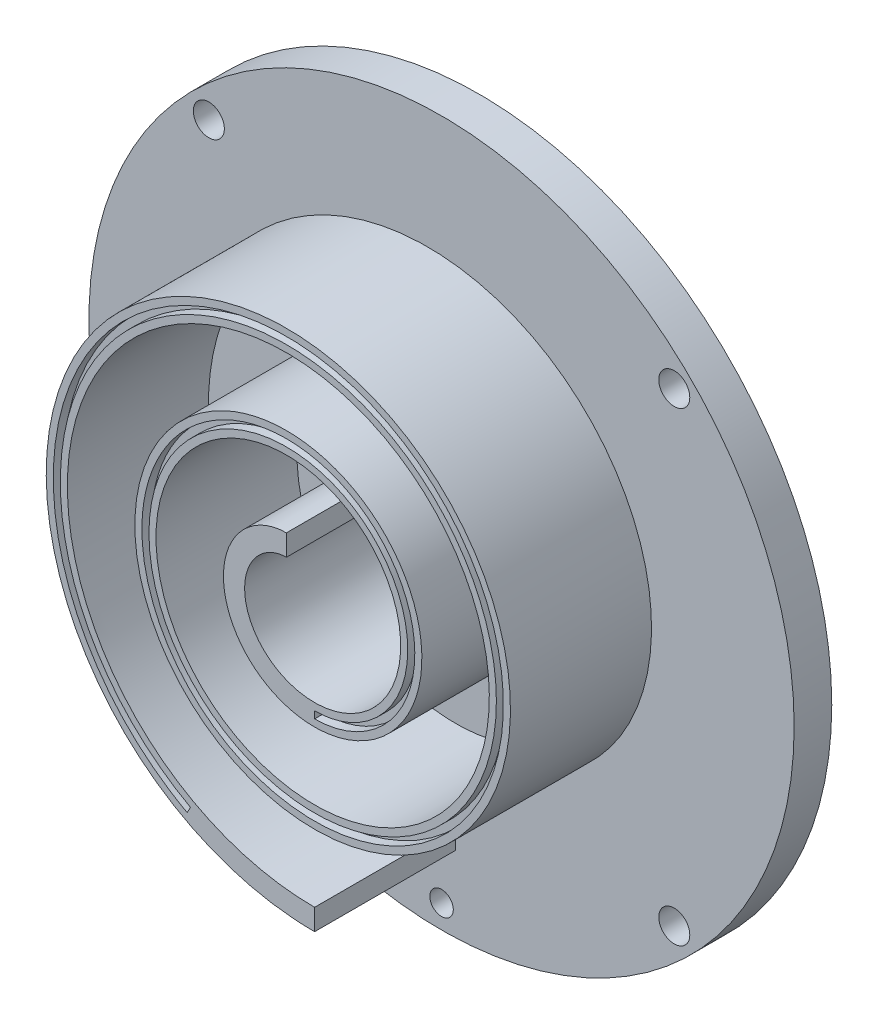
SolidWorks part; units mm, degrees
ref_plane "前视基准面" through (0, 0, 0) normal (0, 0, 1) x (1, 0, 0)
ref_plane "上视基准面" through (0, 0, 0) normal (0, 1, 0) x (1, 0, 0)
ref_plane "右视基准面" through (0, 0, 0) normal (1, 0, 0) x (0, 0, -1)
sketch "草图1" plane through (0, 0, 0) normal (0, 0, 1) x (1, 0, 0)
  circle A0 centre (0, 0) radius 75
extrude "凸台-拉伸1" add sketch "草图1" along normal blind 8
ref_plane "基准面1" through (0, 0, 8) normal (0, 0, 1) x (1, 0, 0)
sketch "草图2" plane through (0, 0, 8) normal (0, 0, 1) x (1, 0, 0)
  line L0 (3, -54.2987) -> (3, -58.7973)
  line L1 (3, -58.7973) -> (3, -58.7987)
  line L2 (-3, 11.6748) -> (-3, 7.1747)
  spline S0 degree 3 poles (-3, 7.1747) (-3.301, 7.1637) (-3.9181, 7.1413) (-4.8518, 6.9591) (-5.8002, 6.6592) (-6.7457, 6.224) (-7.6694, 5.6534) (-8.5516, 4.9455) (-9.3721, 4.1026) (-9.9821, 3.299) (-10.4206, 2.5966) (-10.7247, 2.0355) (-10.9986, 1.4466) (-11.2401, 0.8315) (-11.4468, 0.192) (-11.6168, -0.4699) (-11.7479, -1.1521) (-11.8385, -1.8523) (-11.8867, -2.568) (-11.891, -3.2966) (-11.85, -4.0353) (-11.7624, -4.7814) (-11.6273, -5.5319) (-11.4437, -6.2836) (-11.211, -7.0334) (-10.9288, -7.7781) (-10.5968, -8.5144) (-10.215, -9.239) (-9.7837, -9.9485) (-9.3031, -10.6394) (-8.7742, -11.3084) (-8.1976, -11.9522) (-7.5746, -12.5673) (-6.9066, -13.1506) (-6.1951, -13.6986) (-5.442, -14.2083) (-4.6493, -14.6767) (-3.8193, -15.1007) (-2.9545, -15.4775) (-2.0576, -15.8044) (-1.1316, -16.0789) (-0.1794, -16.2987) (0.7956, -16.4616) (1.79, -16.5655) (2.8002, -16.6087) (3.8224, -16.5898) (4.8528, -16.5072) (5.8874, -16.3601) (6.9221, -16.1475) (7.9527, -15.8689) (8.975, -15.524) (9.9847, -15.1128) (10.9775, -14.6356) (11.949, -14.0929) (12.8949, -13.4855) (13.8109, -12.8146) (14.6927, -12.0816) (15.5361, -11.2882) (16.3371, -10.4363) (17.0915, -9.5281) (17.7955, -8.5663) (18.4453, -7.5537) (19.0373, -6.4932) (19.568, -5.3883) (20.0342, -4.2424) (20.433, -3.0593) (20.7613, -1.8432) (21.0167, -0.5981) (21.1969, 0.6715) (21.2998, 1.961) (21.3237, 3.2657) (21.267, 4.5807) (21.1286, 5.901) (20.9076, 7.2214) (20.6036, 8.5368) (20.2162, 9.842) (19.7457, 11.1315) (19.1924, 12.4001) (18.5573, 13.6425) (17.8414, 14.8533) (17.0463, 16.0273) (16.1738, 17.1593) (15.2261, 18.2442) (14.2057, 19.2769) (13.1155, 20.2527) (11.9586, 21.1668) (10.7386, 22.0146) (9.4592, 22.792) (8.1246, 23.4947) (6.7391, 24.1188) (5.3073, 24.6609) (3.8343, 25.1174) (2.325, 25.4855) (0.7848, 25.7623) (-0.7806, 25.9454) (-2.3656, 26.0329) (-3.9643, 26.0229) (-5.5706, 25.9141) (-7.1785, 25.7056) (-8.7816, 25.3968) (-10.3737, 24.9874) (-11.9485, 24.4777) (-13.4996, 23.8682) (-15.0206, 23.16) (-16.5053, 22.3545) (-17.9474, 21.4535) (-19.3407, 20.4591) (-20.6791, 19.3741) (-21.9569, 18.2014) (-23.1682, 16.9445) (-24.3074, 15.607) (-25.3693, 14.1931) (-26.3487, 12.7074) (-27.2408, 11.1546) (-28.041, 9.5399) (-28.7451, 7.8687) (-29.3491, 6.1469) (-29.8495, 4.3803) (-30.243, 2.5754) (-30.5268, 0.7386) (-30.6985, -1.1234) (-30.756, -3.0038) (-30.6978, -4.8954) (-30.5226, -6.7911) (-30.2298, -8.6837) (-29.8191, -10.5659) (-29.2907, -12.4301) (-28.6452, -14.2692) (-27.8838, -16.0756) (-27.008, -17.842) (-26.0199, -19.5612) (-24.922, -21.226) (-23.7173, -22.8294) (-22.4092, -24.3645) (-21.0017, -25.8246) (-19.4989, -27.2033) (-17.9056, -28.4944) (-16.2269, -29.6919) (-14.4684, -30.7902) (-12.6359, -31.784) (-10.7357, -32.6683) (-8.7743, -33.4386) (-6.7586, -34.0906) (-4.6958, -34.6206) (-2.5932, -35.0253) (-0.4586, -35.3017) (1.7002, -35.4474) (3.8752, -35.4606) (6.0582, -35.3398) (8.2408, -35.084) (10.4149, -34.6928) (12.5718, -34.1664) (14.7032, -33.5054) (16.8005, -32.7109) (18.8556, -31.7846) (20.8599, -30.7288) (22.8054, -29.5463) (24.684, -28.2402) (26.4879, -26.8143) (28.2093, -25.273) (29.8409, -23.621) (31.3756, -21.8635) (32.8065, -20.0063) (34.1272, -18.0555) (35.3315, -16.0176) (36.4138, -13.8996) (37.3686, -11.709) (38.1912, -9.4532) (38.8771, -7.1405) (39.4224, -4.779) (39.8238, -2.3774) (40.0784, 0.0556) (40.1837, 2.5108) (40.1381, 4.9792) (39.9403, 7.4515) (39.5897, 9.9181) (39.0862, 12.3697) (38.4304, 14.7967) (37.6234, 17.1896) (36.6669, 19.539) (35.5632, 21.8355) (34.3153, 24.0698) (32.9267, 26.233) (31.4013, 28.316) (30.0215, 29.9762) (28.8545, 31.2558) (27.9473, 32.1913) (27.0097, 33.1004) (26.0427, 33.9823) (25.0468, 34.836) (24.0231, 35.6605) (22.9723, 36.4549) (21.8953, 37.2183) (20.7931, 37.9499) (19.6665, 38.6488) (18.5166, 39.3143) (17.3443, 39.9455) (16.1507, 40.5417) (14.9368, 41.1022) (13.7037, 41.6263) (12.4524, 42.1133) (11.1841, 42.5627) (9.9, 42.9738) (8.6011, 43.3462) (7.2887, 43.6792) (5.964, 43.9724) (4.628, 44.2253) (3.2822, 44.4376) (1.9277, 44.6089) (0.5658, 44.7388) (-0.8024, 44.827) (-2.1753, 44.8733) (-3.5519, 44.8775) (-4.9308, 44.8394) (-6.3107, 44.7589) (-7.6903, 44.6358) (-9.0683, 44.4701) (-10.4433, 44.2618) (-11.814, 44.0109) (-13.1792, 43.7175) (-14.5375, 43.3817) (-15.8876, 43.0036) (-17.2281, 42.5834) (-18.5578, 42.1214) (-19.8753, 41.6178) (-21.1793, 41.0729) (-22.4686, 40.4871) (-23.7419, 39.8608) (-24.9978, 39.1944) (-26.2352, 38.4884) (-27.4527, 37.7433) (-28.6492, 36.9597) (-29.8233, 36.1381) (-30.974, 35.2792) (-32.1, 34.3836) (-33.2002, 33.4521) (-34.2734, 32.4854) (-35.3184, 31.4842) (-36.3342, 30.4495) (-37.3197, 29.382) (-38.2739, 28.2827) (-39.1957, 27.1524) (-40.0841, 25.9922) (-40.9381, 24.8029) (-41.7568, 23.5857) (-42.5393, 22.3415) (-43.2847, 21.0715) (-43.9922, 19.7767) (-44.6608, 18.4583) (-45.2899, 17.1175) (-45.8788, 15.7554) (-46.4265, 14.3733) (-46.9326, 12.9723) (-47.3964, 11.5538) (-47.8172, 10.1191) (-48.1946, 8.6693) (-48.5279, 7.206) (-48.8167, 5.7303) (-49.0605, 4.2437) (-49.259, 2.7475) (-49.4119, 1.243) (-49.5187, -0.2682) (-49.5791, -1.7847) (-49.5931, -3.3053) (-49.5604, -4.8284) (-49.4808, -6.3526) (-49.3543, -7.8764) (-49.1807, -9.3985) (-48.9602, -10.9173) (-48.6926, -12.4314) (-48.3782, -13.9394) (-48.017, -15.4397) (-47.6092, -16.931) (-47.155, -18.4118) (-46.6547, -19.8806) (-46.1086, -21.336) (-45.5171, -22.7766) (-44.8804, -24.201) (-44.1992, -25.6077) (-43.4738, -26.9953) (-42.7048, -28.3625) (-41.8927, -29.7079) (-41.0383, -31.0301) (-40.1421, -32.3278) (-39.2048, -33.5997) (-38.2272, -34.8444) (-37.21, -36.0608) (-36.1542, -37.2474) (-35.0605, -38.4032) (-33.9299, -39.5269) (-32.7633, -40.6173) (-31.5616, -41.6733) (-30.326, -42.6937) (-29.0574, -43.6774) (-27.7569, -44.6235) (-26.4257, -45.5308) (-25.0649, -46.3983) (-23.6757, -47.2251) (-22.2593, -48.0104) (-20.817, -48.753) (-19.3501, -49.4523) (-17.8598, -50.1075) (-16.3475, -50.7176) (-14.8145, -51.2821) (-13.2623, -51.8001) (-11.6922, -52.2711) (-10.1056, -52.6945) (-8.5041, -53.0696) (-6.889, -53.396) (-5.262, -53.6732) (-3.6243, -53.9006) (-1.9777, -54.0783) (-0.3236, -54.2046) (1.3365, -54.2839) (2.4452, -54.2938) (3, -54.2987) knots 0 0 0 0 0.001869 0.003832 0.005889 0.008039 0.010283 0.01262 0.01505 0.017575 0.018872 0.020194 0.021538 0.022906 0.024297 0.025712 0.02715 0.028612 0.030097 0.031605 0.033137 0.034692 0.03627 0.037872 0.039498 0.041146 0.042818 0.044514 0.046233 0.047975 0.04974 0.051529 0.053342 0.055178 0.057037 0.05892 0.060825 0.062755 0.064708 0.066684 0.068683 0.070706 0.072753 0.074822 0.076916 0.079032 0.081172 0.083335 0.085522 0.087732 0.089966 0.092223 0.094503 0.096807 0.099134 0.101484 0.103858 0.106255 0.108676 0.11112 0.113587 0.116078 0.118592 0.12113 0.123691 0.126275 0.128883 0.131514 0.134169 0.136847 0.139548 0.142273 0.145021 0.147793 0.150587 0.153406 0.156248 0.159113 0.162001 0.164913 0.167848 0.170807 0.173789 0.176795 0.179823 0.182876 0.185951 0.18905 0.192173 0.195319 0.198488 0.20168 0.204896 0.208136 0.211399 0.214685 0.217994 0.221327 0.224684 0.228063 0.231467 0.234893 0.238343 0.241816 0.245313 0.248833 0.252377 0.255944 0.259534 0.263148 0.266785 0.270445 0.274129 0.277836 0.281567 0.285321 0.289098 0.292899 0.296723 0.300571 0.304442 0.308337 0.312254 0.316195 0.32016 0.324148 0.328159 0.332194 0.336252 0.340334 0.344439 0.348567 0.352719 0.356894 0.361093 0.365314 0.36956 0.373828 0.37812 0.382436 0.386775 0.391137 0.395523 0.399932 0.404364 0.40882 0.413299 0.417802 0.422328 0.426877 0.43145 0.436046 0.440666 0.445309 0.449975 0.454665 0.459378 0.464115 0.468875 0.473658 0.478465 0.483295 0.488148 0.493025 0.497926 0.502849 0.507796 0.512767 0.517761 0.522778 0.527819 0.532883 0.53797 0.543081 0.548215 0.553373 0.558554 0.563758 0.568986 0.574237 0.579512 0.58481 0.590131 0.595476 0.600844 0.603537 0.606236 0.608941 0.611652 0.614369 0.617091 0.619819 0.622553 0.625293 0.628039 0.630791 0.633548 0.636312 0.639081 0.641856 0.644637 0.647424 0.650216 0.653015 0.655819 0.658629 0.661445 0.664267 0.667095 0.669928 0.672768 0.675613 0.678464 0.681321 0.684184 0.687052 0.689927 0.692807 0.695693 0.698585 0.701483 0.704387 0.707297 0.710212 0.713133 0.71606 0.718993 0.721932 0.724877 0.727827 0.730784 0.733746 0.736714 0.739688 0.742668 0.745653 0.748645 0.751642 0.754645 0.757654 0.760669 0.76369 0.766717 0.769749 0.772787 0.775831 0.778881 0.781937 0.784999 0.788066 0.79114 0.794219 0.797304 0.800395 0.803491 0.806594 0.809703 0.812817 0.815937 0.819063 0.822195 0.825332 0.828476 0.831625 0.834781 0.837942 0.841109 0.844281 0.84746 0.850645 0.853835 0.857031 0.860233 0.863441 0.866655 0.869874 0.8731 0.876331 0.879568 0.882811 0.88606 0.889315 0.892575 0.895841 0.899114 0.902392 0.905676 0.908965 0.912261 0.915563 0.91887 0.922183 0.925502 0.928827 0.932158 0.935494 0.938837 0.942185 0.945539 0.948899 0.952265 0.955636 0.959014 0.962397 0.965786 0.969181 0.972582 0.975989 0.979402 0.98282 0.986244 0.989674 0.99311 0.996552 1 1 1 1
  spline S1 degree 3 poles (3, -58.7987) (2.3992, -58.7934) (1.1984, -58.7827) (-0.5996, -58.6968) (-2.3914, -58.56) (-4.1753, -58.3675) (-5.9497, -58.121) (-7.7129, -57.8207) (-9.4632, -57.4669) (-11.1992, -57.0603) (-12.9192, -56.6014) (-14.6215, -56.0907) (-16.3047, -55.5289) (-17.9673, -54.9167) (-19.6076, -54.2549) (-21.2243, -53.5442) (-22.8159, -52.7855) (-24.381, -51.9796) (-25.9181, -51.1275) (-27.4259, -50.23) (-28.9031, -49.2882) (-30.3484, -48.3032) (-31.7606, -47.2759) (-33.1383, -46.2076) (-34.4804, -45.0992) (-35.7858, -43.9521) (-37.0533, -42.7674) (-38.2818, -41.5464) (-39.4704, -40.2903) (-40.618, -39.0005) (-41.7237, -37.6782) (-42.7866, -36.3249) (-43.8058, -34.9419) (-44.7805, -33.5306) (-45.7099, -32.0924) (-46.5933, -30.6288) (-47.43, -29.1412) (-48.2193, -27.6312) (-48.9607, -26.1003) (-49.6537, -24.5499) (-50.2977, -22.9815) (-50.8923, -21.3968) (-51.4372, -19.7973) (-51.9318, -18.1845) (-52.376, -16.5601) (-52.7695, -14.9255) (-53.1122, -13.2823) (-53.4037, -11.6323) (-53.6441, -9.9768) (-53.8333, -8.3176) (-53.9713, -6.6561) (-54.058, -4.9941) (-54.0937, -3.3329) (-54.0785, -1.6743) (-54.0125, -0.0197) (-53.896, 1.6292) (-53.7292, 3.271) (-53.5125, 4.9041) (-53.2463, 6.5269) (-52.931, 8.1381) (-52.567, 9.7361) (-52.1549, 11.3195) (-51.6952, 12.8867) (-51.1885, 14.4365) (-50.6355, 15.9673) (-50.0369, 17.4778) (-49.3933, 18.9666) (-48.7055, 20.4324) (-47.9744, 21.8739) (-47.2007, 23.2899) (-46.3854, 24.679) (-45.5294, 26.04) (-44.6336, 27.3718) (-43.6991, 28.6732) (-42.7267, 29.9431) (-41.7177, 31.1804) (-40.673, 32.384) (-39.5938, 33.5529) (-38.4813, 34.6862) (-37.3365, 35.7828) (-36.1608, 36.842) (-34.9553, 37.8627) (-33.7212, 38.8442) (-32.4599, 39.7857) (-31.1725, 40.6865) (-29.8606, 41.5458) (-28.5253, 42.3629) (-27.168, 43.1373) (-25.7901, 43.8685) (-24.3929, 44.5557) (-22.9779, 45.1986) (-21.5465, 45.7967) (-20.1, 46.3496) (-18.6399, 46.8569) (-17.1676, 47.3184) (-15.6846, 47.7338) (-14.1923, 48.1027) (-12.6921, 48.4251) (-11.1855, 48.7009) (-9.674, 48.9299) (-8.1589, 49.112) (-6.6418, 49.2474) (-5.1241, 49.336) (-3.6072, 49.3779) (-2.0925, 49.3733) (-0.5815, 49.3223) (0.9244, 49.2252) (2.4238, 49.0821) (3.9153, 48.8936) (5.3975, 48.6598) (6.8691, 48.3811) (8.3286, 48.0581) (9.7749, 47.6911) (11.2065, 47.2807) (12.6221, 46.8275) (14.0205, 46.332) (15.4005, 45.7949) (16.7607, 45.2168) (18.0999, 44.5984) (19.4171, 43.9405) (20.7109, 43.2438) (21.9803, 42.5092) (23.2242, 41.7375) (24.4415, 40.9295) (25.6311, 40.0863) (26.7921, 39.2086) (27.9233, 38.2975) (29.024, 37.354) (30.0931, 36.379) (31.1298, 35.3737) (32.1331, 34.3391) (33.1024, 33.2763) (34.0368, 32.1864) (34.9355, 31.0706) (35.7979, 29.9299) (36.6232, 28.7657) (37.4109, 27.579) (38.1603, 26.3711) (38.8709, 25.1433) (39.5422, 23.8967) (40.1736, 22.6326) (40.7648, 21.3523) (41.3153, 20.0571) (41.8249, 18.7483) (42.293, 17.4271) (42.7196, 16.0948) (43.1044, 14.7528) (43.4471, 13.4024) (43.7476, 12.0449) (44.0057, 10.6815) (44.2216, 9.3137) (44.3949, 7.9426) (44.5259, 6.5698) (44.6146, 5.1963) (44.6609, 3.8237) (44.6652, 2.453) (44.6274, 1.0857) (44.5479, -0.277) (44.4269, -1.6337) (44.2647, -2.9834) (44.0615, -4.3246) (43.8178, -5.6562) (43.534, -6.9769) (43.2105, -8.2856) (42.8478, -9.5809) (42.4463, -10.8619) (42.0067, -12.1273) (41.5294, -13.3759) (41.0152, -14.6068) (40.4646, -15.8187) (39.8784, -17.0106) (39.2572, -18.1815) (38.6017, -19.3303) (37.9128, -20.456) (37.1913, -21.5578) (36.4379, -22.6345) (35.6535, -23.6854) (34.8391, -24.7095) (33.9954, -25.706) (32.8341, -26.9953) (31.3142, -28.5342) (29.387, -30.2597) (27.3664, -31.8569) (25.2609, -33.3206) (23.0794, -34.6467) (20.8306, -35.8312) (18.5237, -36.8709) (16.168, -37.7633) (13.7727, -38.5061) (11.3475, -39.098) (8.9016, -39.5381) (6.4445, -39.826) (3.9857, -39.9621) (1.5345, -39.9472) (-0.9, -39.7828) (-3.3085, -39.4709) (-5.6823, -39.014) (-8.0127, -38.4153) (-10.2912, -37.6782) (-12.5097, -36.8069) (-14.6604, -35.806) (-16.7357, -34.6805) (-18.7285, -33.4359) (-20.6321, -32.0779) (-22.44, -30.6129) (-24.1463, -29.0474) (-25.7456, -27.3884) (-27.2328, -25.643) (-28.6034, -23.8188) (-29.8534, -21.9233) (-30.9791, -19.9646) (-31.9776, -17.9507) (-32.8463, -15.8897) (-33.5833, -13.79) (-34.187, -11.66) (-34.6566, -9.5079) (-34.9916, -7.3423) (-35.1921, -5.1715) (-35.2588, -3.0038) (-35.1928, -0.8473) (-34.9958, 1.2898) (-34.6697, 3.3996) (-34.2173, 5.4744) (-33.6417, 7.5067) (-32.9462, 9.4892) (-32.1348, 11.415) (-31.2119, 13.2772) (-30.1822, 15.0695) (-29.0508, 16.7859) (-27.8229, 18.4206) (-26.5045, 19.9684) (-25.1016, 21.4243) (-23.6203, 22.7837) (-22.0672, 24.0427) (-20.449, 25.1974) (-18.7726, 26.2448) (-17.0451, 27.1821) (-15.2737, 28.0068) (-13.4655, 28.7173) (-11.6279, 29.3121) (-9.7682, 29.7902) (-7.8938, 30.1513) (-6.012, 30.3953) (-4.13, 30.5227) (-2.2551, 30.5344) (-0.3943, 30.4317) (1.4455, 30.2164) (3.2576, 29.8907) (5.0352, 29.4571) (6.7722, 28.9188) (8.4622, 28.2789) (10.0996, 27.5412) (11.6787, 26.7098) (13.1941, 25.789) (14.641, 24.7835) (16.0146, 23.6981) (17.3106, 22.5381) (18.5251, 21.3088) (19.6546, 20.0159) (20.6957, 18.6651) (21.6457, 17.2623) (22.5021, 15.8137) (23.263, 14.3253) (23.9266, 12.8035) (24.4918, 11.2544) (24.9577, 9.6844) (25.324, 8.0999) (25.5905, 6.5069) (25.7576, 4.9119) (25.8262, 3.3209) (25.7972, 1.7401) (25.6723, 0.1752) (25.4533, -1.3679) (25.1423, -2.8836) (24.7419, -4.3664) (24.2549, -5.8112) (23.6845, -7.213) (23.0342, -8.5669) (22.3075, -9.8686) (21.5085, -11.1137) (20.6413, -12.2984) (19.7103, -13.419) (18.7201, -14.4721) (17.6754, -15.4549) (16.5811, -16.3644) (15.4423, -17.1985) (14.2639, -17.9551) (13.0512, -18.6325) (11.8094, -19.2293) (10.5439, -19.7447) (9.2598, -20.1778) (7.9625, -20.5284) (6.6572, -20.7966) (5.3491, -20.9826) (4.0433, -21.0872) (2.7449, -21.1112) (1.4587, -21.0561) (0.1896, -20.9234) (-1.0579, -20.715) (-2.2792, -20.4331) (-3.4701, -20.08) (-4.6265, -19.6584) (-5.7445, -19.1712) (-6.8205, -18.6215) (-7.851, -18.0126) (-8.8328, -17.348) (-9.7631, -16.6313) (-10.6393, -15.8664) (-11.4588, -15.0571) (-12.2196, -14.2075) (-12.9198, -13.3217) (-13.558, -12.404) (-14.1329, -11.4584) (-14.6434, -10.4894) (-15.0889, -9.5013) (-15.4689, -8.4982) (-15.7834, -7.4845) (-16.0325, -6.4644) (-16.2165, -5.4421) (-16.3362, -4.4217) (-16.3925, -3.4071) (-16.3865, -2.4023) (-16.3196, -1.411) (-16.1936, -0.4368) (-16.0102, 0.5166) (-15.7715, 1.4461) (-15.4797, 2.3485) (-15.1372, 3.2207) (-14.7467, 4.06) (-14.3109, 4.8639) (-13.8325, 5.63) (-13.3147, 6.3561) (-12.7604, 7.0403) (-12.1728, 7.6809) (-11.5552, 8.2764) (-10.9109, 8.8256) (-10.2431, 9.3275) (-9.5552, 9.7812) (-8.8506, 10.1863) (-8.1326, 10.5424) (-7.4046, 10.8494) (-6.6697, 11.1074) (-5.9313, 11.3168) (-5.1925, 11.4783) (-4.4563, 11.5916) (-3.7258, 11.6618) (-3.2407, 11.6705) (-3, 11.6748) knots 0 0 0 0 0.003257 0.006508 0.009755 0.012996 0.016233 0.019464 0.02269 0.025911 0.029127 0.032338 0.035544 0.038745 0.04194 0.045131 0.048316 0.051496 0.054671 0.057841 0.061006 0.064166 0.067321 0.07047 0.073615 0.076754 0.079889 0.083018 0.086142 0.089261 0.092375 0.095484 0.098588 0.101686 0.10478 0.107868 0.110951 0.11403 0.117103 0.120171 0.123234 0.126291 0.129344 0.132392 0.135434 0.138472 0.141504 0.144531 0.147553 0.15057 0.153582 0.156589 0.159591 0.162587 0.165579 0.168565 0.171546 0.174522 0.177493 0.180459 0.18342 0.186376 0.189327 0.192272 0.195213 0.198148 0.201078 0.204003 0.206924 0.209838 0.212748 0.215653 0.218553 0.221447 0.224337 0.227221 0.2301 0.232974 0.235843 0.238707 0.241566 0.24442 0.247269 0.250112 0.25295 0.255784 0.258612 0.261435 0.264253 0.267066 0.269874 0.272677 0.275474 0.278267 0.281054 0.283836 0.286614 0.289386 0.292153 0.294915 0.297671 0.300423 0.30317 0.305911 0.308647 0.311379 0.314105 0.316826 0.319542 0.322253 0.324959 0.327659 0.330355 0.333045 0.335731 0.338411 0.341086 0.343756 0.346421 0.349081 0.351736 0.354385 0.35703 0.359669 0.362304 0.364933 0.367557 0.370176 0.37279 0.375399 0.378003 0.380601 0.383195 0.385783 0.388366 0.390945 0.393518 0.396086 0.398649 0.401207 0.403759 0.406307 0.408849 0.411387 0.413919 0.416446 0.418968 0.421485 0.423997 0.426504 0.429006 0.431502 0.433994 0.43648 0.438962 0.441438 0.443909 0.446375 0.448836 0.451291 0.453742 0.456188 0.458628 0.461064 0.463494 0.465919 0.468339 0.470754 0.473164 0.475569 0.477968 0.480363 0.482752 0.485137 0.487516 0.48989 0.492259 0.494623 0.496982 0.499336 0.504027 0.508698 0.513349 0.51798 0.52259 0.527179 0.531748 0.536297 0.540826 0.545334 0.549821 0.554288 0.558735 0.563161 0.567567 0.571953 0.576318 0.580663 0.584987 0.589291 0.593575 0.597838 0.60208 0.606303 0.610505 0.614686 0.618847 0.622988 0.627108 0.631208 0.635287 0.639346 0.643385 0.647403 0.651401 0.655379 0.659336 0.663272 0.667189 0.671084 0.67496 0.678815 0.682649 0.686464 0.690257 0.694031 0.697784 0.701516 0.705228 0.70892 0.712592 0.716243 0.719873 0.723483 0.727073 0.730642 0.734191 0.73772 0.741228 0.744716 0.748183 0.75163 0.755056 0.758462 0.761848 0.765213 0.768558 0.771883 0.775187 0.77847 0.781734 0.784977 0.788199 0.791401 0.794583 0.797744 0.800885 0.804005 0.807105 0.810185 0.813244 0.816283 0.819301 0.822299 0.825277 0.828234 0.831171 0.834087 0.836983 0.839859 0.842714 0.845549 0.848363 0.851157 0.85393 0.856683 0.859416 0.862129 0.86482 0.867492 0.870143 0.872774 0.875384 0.877974 0.880543 0.883092 0.885621 0.888129 0.890617 0.893085 0.895532 0.897958 0.900365 0.902751 0.905116 0.907461 0.909786 0.91209 0.914374 0.916637 0.91888 0.921103 0.923305 0.925487 0.927648 0.929789 0.93191 0.93401 0.936089 0.938149 0.940188 0.942206 0.944204 0.946182 0.948139 0.950076 0.951993 0.953889 0.955765 0.95762 0.959455 0.961269 0.963063 0.964837 0.96659 0.968323 0.970036 0.971728 0.9734 0.975051 0.976682 0.978292 0.979882 0.981452 0.983001 0.98453 0.986038 0.987526 0.988994 0.990441 0.991868 0.993274 0.99466 0.996026 0.997371 0.998696 1 1 1 1
extrude "凸台-拉伸2" add sketch "草图2" along normal blind 30
ref_plane "基准面2" through (0, 0, 38) normal (0, 0, 1) x (1, 0, 0)
sketch "草图3" plane through (0, 0, 38) normal (0, 0, 1) x (1, 0, 0)
  line L0 (-23.3994, -49.0898) -> (-24.1187, -50.4063)
  line L1 (3, -19.5996) -> (3, -18.0996)
  spline S0 degree 3 poles (3, -18.0996) (3.2855, -18.0957) (3.8587, -18.0878) (4.7198, -18.0244) (5.5838, -17.9227) (6.4486, -17.7785) (7.3121, -17.5925) (8.1724, -17.3643) (9.0273, -17.0937) (9.8747, -16.7809) (10.7127, -16.426) (11.5389, -16.029) (12.3514, -15.5904) (13.1481, -15.1105) (13.9268, -14.59) (14.6855, -14.0293) (15.4221, -13.4294) (16.1346, -12.7909) (16.8209, -12.1149) (17.4792, -11.4024) (18.1074, -10.6546) (18.7038, -9.8728) (19.2664, -9.0582) (19.7936, -8.2123) (20.2836, -7.3368) (20.7347, -6.4331) (21.1455, -5.5031) (21.5144, -4.5486) (21.8401, -3.5714) (22.1211, -2.5735) (22.3563, -1.557) (22.5446, -0.524) (22.6848, 0.5233) (22.7762, 1.5827) (22.8177, 2.6519) (22.8088, 3.7286) (22.7488, 4.8103) (22.6372, 5.8946) (22.4737, 6.979) (22.258, 8.061) (21.9898, 9.1382) (21.6694, 10.2079) (21.2967, 11.2676) (20.8719, 12.3148) (20.3955, 13.3468) (19.8679, 14.3611) (19.2898, 15.3553) (18.6618, 16.3267) (17.9849, 17.2728) (17.26, 18.1912) (16.4883, 19.0795) (15.671, 19.9353) (14.8095, 20.7562) (13.9052, 21.5399) (12.9597, 22.2844) (11.9748, 22.9873) (10.9522, 23.6466) (9.894, 24.2604) (8.8021, 24.8267) (7.6787, 25.3437) (6.526, 25.8097) (5.3463, 26.2231) (4.142, 26.5823) (2.9157, 26.886) (1.6699, 27.1329) (0.4073, 27.3218) (-0.8695, 27.4517) (-2.1576, 27.5216) (-3.4542, 27.5308) (-4.7566, 27.4786) (-6.0616, 27.3646) (-7.3664, 27.1883) (-8.6681, 26.9495) (-9.9635, 26.6482) (-11.2497, 26.2843) (-12.5237, 25.8581) (-13.7823, 25.37) (-15.0227, 24.8203) (-16.2418, 24.2099) (-17.4365, 23.5395) (-18.604, 22.8099) (-19.7413, 22.0224) (-20.8456, 21.1781) (-21.9139, 20.2785) (-22.9436, 19.3249) (-23.9318, 18.3192) (-24.876, 17.263) (-25.7736, 16.1584) (-26.6221, 15.0073) (-27.4191, 13.8119) (-28.1624, 12.5747) (-28.8497, 11.2979) (-29.479, 9.9841) (-30.0482, 8.636) (-30.5556, 7.2563) (-30.9995, 5.8479) (-31.3781, 4.4137) (-31.6902, 2.9568) (-31.9344, 1.4801) (-32.1095, -0.013) (-32.2146, -1.5194) (-32.2486, -3.0357) (-32.2111, -4.5586) (-32.1013, -6.0846) (-31.919, -7.6105) (-31.6639, -9.1326) (-31.336, -10.6475) (-30.9353, -12.1518) (-30.4621, -13.6418) (-29.917, -15.1142) (-29.3005, -16.5653) (-28.6134, -17.9918) (-27.8567, -19.3903) (-27.0315, -20.7572) (-26.1391, -22.0892) (-25.181, -23.3831) (-24.1587, -24.6356) (-23.0742, -25.8435) (-21.9292, -27.0037) (-20.7259, -28.1131) (-19.4666, -29.1689) (-18.1536, -30.1683) (-16.7896, -31.1085) (-15.377, -31.9868) (-13.9189, -32.8009) (-12.418, -33.5484) (-10.8775, -34.227) (-9.3005, -34.8346) (-7.6903, -35.3694) (-6.0502, -35.8295) (-4.3838, -36.2133) (-2.6947, -36.5194) (-0.9863, -36.7465) (0.7375, -36.8933) (2.4729, -36.959) (4.2162, -36.9428) (5.9634, -36.8442) (7.7107, -36.6626) (9.4541, -36.3979) (11.1896, -36.05) (12.9133, -35.6191) (14.6211, -35.1056) (16.3091, -34.51) (17.9734, -33.8329) (19.6099, -33.0755) (21.2149, -32.2386) (22.7844, -31.3237) (24.3147, -30.3323) (25.8019, -29.266) (27.2425, -28.1266) (28.6329, -26.9163) (29.9695, -25.6372) (31.2489, -24.2917) (32.4679, -22.8823) (33.6232, -21.4119) (34.7118, -19.8832) (35.7308, -18.2993) (36.6774, -16.6634) (37.549, -14.9788) (38.3429, -13.249) (39.057, -11.4774) (39.689, -9.6679) (40.237, -7.8243) (40.699, -5.9504) (41.0736, -4.0503) (41.3592, -2.128) (41.5545, -0.1878) (41.6586, 1.7662) (41.6706, 3.7295) (41.5897, 5.6978) (41.4156, 7.6669) (41.1481, 9.6321) (40.787, 11.5891) (40.3326, 13.5334) (39.7853, 15.4606) (39.1457, 17.3661) (38.4146, 19.2456) (37.593, 21.0947) (36.6822, 22.9089) (35.6837, 24.684) (34.5991, 26.4158) (33.4303, 28.1) (32.1795, 29.7326) (30.8487, 31.3095) (29.4407, 32.8269) (27.9579, 34.2809) (26.4033, 35.6678) (24.7799, 36.9842) (23.0909, 38.2266) (21.3397, 39.3917) (19.5299, 40.4764) (17.665, 41.4778) (15.7491, 42.3931) (13.786, 43.2197) (11.7798, 43.9551) (9.7349, 44.5973) (7.6556, 45.144) (5.5463, 45.5936) (3.4115, 45.9444) (1.256, 46.1949) (-0.9156, 46.3441) (-3.0984, 46.391) (-5.2878, 46.3347) (-7.4786, 46.1749) (-9.6662, 45.9113) (-11.8454, 45.5437) (-14.0115, 45.0725) (-16.1593, 44.498) (-18.2841, 43.821) (-20.3809, 43.0422) (-22.4447, 42.1629) (-24.4709, 41.1845) (-26.4545, 40.1085) (-28.391, 38.9367) (-30.2756, 37.6714) (-32.1039, 36.3146) (-33.8714, 34.869) (-35.5737, 33.3373) (-37.2068, 31.7223) (-38.7664, 30.0273) (-40.2488, 28.2556) (-41.65, 26.4107) (-42.9666, 24.4964) (-44.1949, 22.5165) (-45.3319, 20.475) (-46.3744, 18.3763) (-47.3196, 16.2247) (-48.1647, 14.0248) (-48.9073, 11.7811) (-49.5452, 9.4985) (-50.0763, 7.1819) (-50.4988, 4.8363) (-50.8112, 2.4668) (-51.0122, 0.0785) (-51.1007, -2.3232) (-51.0759, -4.7331) (-50.9371, -7.1459) (-50.6841, -9.556) (-50.3169, -11.9581) (-49.8356, -14.3468) (-49.2406, -16.7166) (-48.5327, -19.0622) (-47.7128, -21.378) (-46.7823, -23.6589) (-45.7424, -25.8994) (-44.5951, -28.0943) (-43.3423, -30.2385) (-41.9862, -32.3269) (-40.5294, -34.3545) (-38.9744, -36.3164) (-37.3244, -38.2079) (-35.5825, -40.0243) (-33.7521, -41.7613) (-31.8368, -43.4143) (-29.8407, -44.9799) (-27.7666, -46.4516) (-25.6239, -47.835) (-24.1416, -48.6712) (-23.3994, -49.0898) knots 0 0 0 0 0.001961 0.003937 0.005928 0.007935 0.009956 0.011993 0.014046 0.016113 0.018196 0.020294 0.022408 0.024536 0.02668 0.028839 0.031013 0.033203 0.035408 0.037628 0.039864 0.042114 0.04438 0.046661 0.048958 0.05127 0.053596 0.055939 0.058296 0.060669 0.063057 0.06546 0.067879 0.070312 0.072762 0.075226 0.077705 0.0802 0.08271 0.085236 0.087776 0.090332 0.092903 0.09549 0.098091 0.100708 0.10334 0.105988 0.10865 0.111328 0.114021 0.11673 0.119453 0.122192 0.124947 0.127716 0.130501 0.133301 0.136116 0.138947 0.141792 0.144653 0.14753 0.150421 0.153328 0.15625 0.159187 0.16214 0.165108 0.168091 0.171089 0.174103 0.177132 0.180176 0.183235 0.18631 0.1894 0.192505 0.195625 0.198761 0.201912 0.205078 0.20826 0.211456 0.214668 0.217896 0.221138 0.224396 0.227669 0.230957 0.234261 0.237579 0.240913 0.244263 0.247627 0.251007 0.254402 0.257812 0.261238 0.264679 0.268135 0.271606 0.275093 0.278595 0.282112 0.285645 0.289192 0.292755 0.296333 0.299927 0.303535 0.307159 0.310799 0.314453 0.318123 0.321808 0.325508 0.329224 0.332954 0.3367 0.340462 0.344238 0.34803 0.351837 0.355659 0.359497 0.36335 0.367218 0.371101 0.375 0.378914 0.382843 0.386787 0.390747 0.394722 0.398712 0.402718 0.406738 0.410774 0.414825 0.418892 0.422974 0.427071 0.431183 0.43531 0.439453 0.443611 0.447784 0.451973 0.456177 0.460396 0.46463 0.46888 0.473145 0.477425 0.48172 0.486031 0.490356 0.494698 0.499054 0.503426 0.507812 0.512215 0.516632 0.521065 0.525513 0.529976 0.534454 0.538948 0.543457 0.547981 0.552521 0.557075 0.561646 0.566231 0.570831 0.575447 0.580078 0.584724 0.589386 0.594063 0.598755 0.603462 0.608185 0.612923 0.617676 0.622444 0.627228 0.632027 0.636841 0.64167 0.646515 0.651375 0.65625 0.66114 0.666046 0.670967 0.675903 0.680855 0.685822 0.690804 0.695801 0.700813 0.705841 0.710884 0.715942 0.721016 0.726105 0.731209 0.736328 0.741463 0.746613 0.751778 0.756958 0.762154 0.767365 0.772591 0.777832 0.783089 0.788361 0.793648 0.79895 0.804268 0.809601 0.814949 0.820312 0.825691 0.831085 0.836494 0.841919 0.847359 0.852814 0.858284 0.86377 0.86927 0.874786 0.880318 0.885864 0.891426 0.897003 0.902596 0.908203 0.913826 0.919464 0.925117 0.930786 0.93647 0.942169 0.947884 0.953613 0.959358 0.965118 0.970894 0.976685 0.982491 0.988312 0.994148 1 1 1 1
  spline S1 degree 3 poles (-24.1187, -50.4063) (-24.8813, -49.976) (-26.4047, -49.1166) (-28.6068, -47.6948) (-30.7386, -46.1822) (-32.7902, -44.573) (-34.7591, -42.8738) (-36.6408, -41.0881) (-38.4317, -39.2206) (-40.1282, -37.2758) (-41.727, -35.2585) (-43.2251, -33.1735) (-44.6197, -31.0258) (-45.9082, -28.8205) (-47.0883, -26.5629) (-48.1579, -24.2583) (-49.1152, -21.9119) (-49.9586, -19.5294) (-50.687, -17.1162) (-51.2992, -14.6778) (-51.7945, -12.2197) (-52.1724, -9.7477) (-52.4328, -7.2672) (-52.5756, -4.7839) (-52.6011, -2.3033) (-52.51, 0.1691) (-52.3031, 2.6279) (-51.9814, 5.0675) (-51.5464, 7.4827) (-50.9995, 9.8682) (-50.3426, 12.2189) (-49.5777, 14.5297) (-48.7072, 16.7957) (-47.7337, 19.0121) (-46.6597, 21.1741) (-45.4883, 23.2773) (-44.2226, 25.3173) (-42.866, 27.29) (-41.422, 29.1912) (-39.8943, 31.0171) (-38.2867, 32.7642) (-36.6034, 34.4288) (-34.8485, 36.0079) (-33.0262, 37.4982) (-31.1412, 38.8971) (-29.1978, 40.2019) (-27.2008, 41.4103) (-25.155, 42.52) (-23.0652, 43.5292) (-20.9363, 44.4362) (-18.7732, 45.2396) (-16.5811, 45.9381) (-14.3649, 46.5309) (-12.1297, 47.0171) (-9.8807, 47.3964) (-7.623, 47.6685) (-5.3616, 47.8335) (-3.1016, 47.8915) (-0.848, 47.8431) (1.3941, 47.6891) (3.6199, 47.4304) (5.8244, 47.0681) (8.0029, 46.6038) (10.1507, 46.0391) (12.2631, 45.3758) (14.3356, 44.6159) (16.3639, 43.7619) (18.3436, 42.8161) (20.2708, 41.7813) (22.1413, 40.6602) (23.9514, 39.4559) (25.6973, 38.1716) (27.3757, 36.8107) (28.983, 35.3767) (30.5163, 33.8732) (31.9725, 32.304) (33.3488, 30.673) (34.6427, 28.9843) (35.8518, 27.242) (36.9739, 25.4503) (38.0071, 23.6135) (38.9496, 21.736) (39.7998, 19.8224) (40.5566, 17.8769) (41.2187, 15.9044) (41.7854, 13.9092) (42.2559, 11.896) (42.6297, 9.8694) (42.9068, 7.8341) (43.0872, 5.7947) (43.1709, 3.7556) (43.1585, 1.7216) (43.0507, -0.3029) (42.8482, -2.3135) (42.5522, -4.3057) (42.164, -6.2753) (41.685, -8.2178) (41.1169, -10.1293) (40.4616, -12.0055) (39.721, -13.8427) (38.8976, -15.6368) (37.9935, -17.3842) (37.0115, -19.0813) (35.9543, -20.7247) (34.8246, -22.3109) (33.6256, -23.837) (32.3603, -25.2998) (31.0322, -26.6966) (29.6445, -28.0246) (28.2008, -29.2813) (26.7047, -30.4646) (25.16, -31.5721) (23.5704, -32.602) (21.9398, -33.5525) (20.2721, -34.422) (18.5713, -35.2092) (16.8416, -35.9129) (15.0869, -36.532) (13.3113, -37.0659) (11.519, -37.5139) (9.7142, -37.8757) (7.9009, -38.151) (6.0833, -38.3399) (4.2654, -38.4426) (2.4514, -38.4594) (0.6453, -38.391) (-1.1489, -38.2382) (-2.9274, -38.0018) (-4.6862, -37.6831) (-6.4215, -37.2834) (-8.1296, -36.8042) (-9.8069, -36.2471) (-11.4499, -35.614) (-13.0552, -34.9069) (-14.6193, -34.128) (-16.1392, -33.2794) (-17.6118, -32.3637) (-19.0341, -31.3834) (-20.4034, -30.3412) (-21.7169, -29.2399) (-22.9721, -28.0825) (-24.1668, -26.872) (-25.2986, -25.6115) (-26.3656, -24.3042) (-27.3658, -22.9535) (-28.2976, -21.5627) (-29.1593, -20.1352) (-29.9497, -18.6746) (-30.6674, -17.1844) (-31.3116, -15.6681) (-31.8813, -14.1294) (-32.3758, -12.572) (-32.7947, -10.9994) (-33.1376, -9.4154) (-33.4044, -7.8235) (-33.5951, -6.2274) (-33.7099, -4.6308) (-33.7492, -3.0372) (-33.7135, -1.4502) (-33.6036, 0.1267) (-33.4202, 1.6901) (-33.1645, 3.2365) (-32.8376, 4.7626) (-32.4408, 6.2652) (-31.9757, 7.741) (-31.4439, 9.1871) (-30.8472, 10.6003) (-30.1873, 11.9779) (-29.4665, 13.3169) (-28.6868, 14.6148) (-27.8506, 15.869) (-26.9601, 17.077) (-26.0179, 18.2365) (-25.0266, 19.3454) (-23.9887, 20.4016) (-22.9072, 21.4032) (-21.7848, 22.3484) (-20.6243, 23.2357) (-19.4289, 24.0634) (-18.2014, 24.8304) (-16.945, 25.5355) (-15.6627, 26.1776) (-14.3576, 26.7558) (-13.033, 27.2696) (-11.692, 27.7182) (-10.3378, 28.1013) (-8.9734, 28.4187) (-7.6022, 28.6702) (-6.2273, 28.856) (-4.8518, 28.9762) (-3.4789, 29.0312) (-2.1115, 29.0214) (-0.7527, 28.9477) (0.5944, 28.8106) (1.9269, 28.6113) (3.2421, 28.3506) (4.5371, 28.0299) (5.8091, 27.6505) (7.0555, 27.2137) (8.2738, 26.7212) (9.4615, 26.1746) (10.6161, 25.5757) (11.7356, 24.9265) (12.8175, 24.2288) (13.86, 23.4848) (14.861, 22.6967) (15.8188, 21.8666) (16.7315, 20.9969) (17.5977, 20.09) (18.4158, 19.1483) (19.1844, 18.1743) (19.9025, 17.1707) (20.5688, 16.1399) (21.1825, 15.0846) (21.7427, 14.0075) (22.2488, 12.9113) (22.7001, 11.7986) (23.0963, 10.6722) (23.4371, 9.5347) (23.7222, 8.3889) (23.9518, 7.2375) (24.1259, 6.0832) (24.2447, 4.9285) (24.3086, 3.7762) (24.3181, 2.6289) (24.2738, 1.489) (24.1764, 0.3591) (24.0267, -0.7583) (23.8258, -1.8609) (23.5746, -2.9463) (23.2744, -4.0122) (22.9264, -5.0565) (22.532, -6.077) (22.0926, -7.0717) (21.6099, -8.0386) (21.0854, -8.9759) (20.5208, -9.8817) (19.9179, -10.7545) (19.2787, -11.5926) (18.6049, -12.3946) (17.8987, -13.159) (17.1619, -13.8846) (16.3968, -14.5703) (15.6054, -15.2149) (14.7898, -15.8175) (13.9523, -16.3774) (13.0951, -16.8937) (12.2203, -17.3659) (11.3303, -17.7935) (10.4272, -18.1761) (9.5134, -18.5134) (8.5911, -18.8052) (7.6625, -19.0516) (6.7298, -19.2524) (5.7953, -19.4083) (4.8611, -19.5183) (3.9294, -19.5869) (3.309, -19.5953) (3, -19.5996) knots 0 0 0 0 0.005774 0.011534 0.017279 0.023009 0.028725 0.034426 0.040113 0.045784 0.051441 0.057084 0.062712 0.068325 0.073923 0.079507 0.085077 0.090631 0.096171 0.101696 0.107207 0.112703 0.118184 0.123651 0.129103 0.13454 0.139963 0.145371 0.150764 0.156143 0.161507 0.166857 0.172191 0.177511 0.182817 0.188108 0.193384 0.198645 0.203892 0.209125 0.214342 0.219545 0.224733 0.229907 0.235066 0.24021 0.24534 0.250455 0.255555 0.260641 0.265712 0.270768 0.27581 0.280837 0.28585 0.290848 0.295831 0.300799 0.305753 0.310692 0.315617 0.320527 0.325422 0.330303 0.335168 0.34002 0.344856 0.349678 0.354486 0.359278 0.364056 0.36882 0.373568 0.378303 0.383022 0.387727 0.392417 0.397092 0.401753 0.406399 0.411031 0.415648 0.42025 0.424837 0.42941 0.433969 0.438512 0.443041 0.447555 0.452055 0.45654 0.46101 0.465466 0.469907 0.474333 0.478745 0.483142 0.487525 0.491892 0.496246 0.500584 0.504908 0.509217 0.513512 0.517791 0.522057 0.526307 0.530543 0.534764 0.538971 0.543163 0.54734 0.551503 0.555651 0.559784 0.563903 0.568007 0.572096 0.576171 0.580231 0.584277 0.588308 0.592324 0.596325 0.600312 0.604284 0.608242 0.612185 0.616113 0.620026 0.623925 0.62781 0.631679 0.635534 0.639374 0.6432 0.647011 0.650808 0.654589 0.658356 0.662109 0.665846 0.66957 0.673278 0.676972 0.680651 0.684315 0.687965 0.6916 0.695221 0.698827 0.702418 0.705995 0.709557 0.713104 0.716637 0.720155 0.723658 0.727147 0.730621 0.73408 0.737525 0.740955 0.74437 0.747771 0.751157 0.754529 0.757885 0.761228 0.764555 0.767868 0.771166 0.77445 0.777719 0.780973 0.784212 0.787437 0.790648 0.793843 0.797024 0.800191 0.803342 0.806479 0.809602 0.812709 0.815803 0.818881 0.821945 0.824994 0.828028 0.831048 0.834053 0.837044 0.84002 0.842981 0.845928 0.848859 0.851777 0.854679 0.857567 0.860441 0.863299 0.866143 0.868973 0.871787 0.874587 0.877373 0.880144 0.8829 0.885641 0.888368 0.89108 0.893777 0.89646 0.899129 0.901782 0.904421 0.907045 0.909655 0.91225 0.91483 0.917396 0.919947 0.922483 0.925005 0.927512 0.930004 0.932482 0.934945 0.937393 0.939827 0.942246 0.94465 0.94704 0.949415 0.951776 0.954122 0.956453 0.958769 0.961071 0.963359 0.965631 0.967889 0.970132 0.972361 0.974575 0.976774 0.978959 0.981129 0.983284 0.985425 0.987551 0.989663 0.991759 0.993842 0.995909 0.997962 1 1 1 1
extrude "切除-拉伸1" cut sketch "草图3" against normal blind 2
sketch "草图4" plane through (0, 0, 0) normal (0, 0, 1) x (1, 0, 0)
  circle A0 centre (0, 0) radius 5
extrude "切除-拉伸2" cut sketch "草图4" against normal mid plane 302
sketch "草图5" plane through (0, 0, 0) normal (0, 0, 1) x (1, 0, 0)
  circle A0 centre (49.4975, 49.4975) radius 3.3
  circle A1 centre (-49.4975, 49.4975) radius 3.3
  circle A2 centre (-49.4975, -49.4975) radius 3.3
  circle A3 centre (49.4975, -49.4975) radius 3.3
extrude "切除-拉伸3" cut sketch "草图5" against normal mid plane 302
sketch "草图6" plane through (0, 0, 0) normal (0, 0, 1) x (1, 0, 0)
  circle A0 centre (0, -70) radius 2.5
extrude "切除-拉伸4" cut sketch "草图6" against normal mid plane 302
